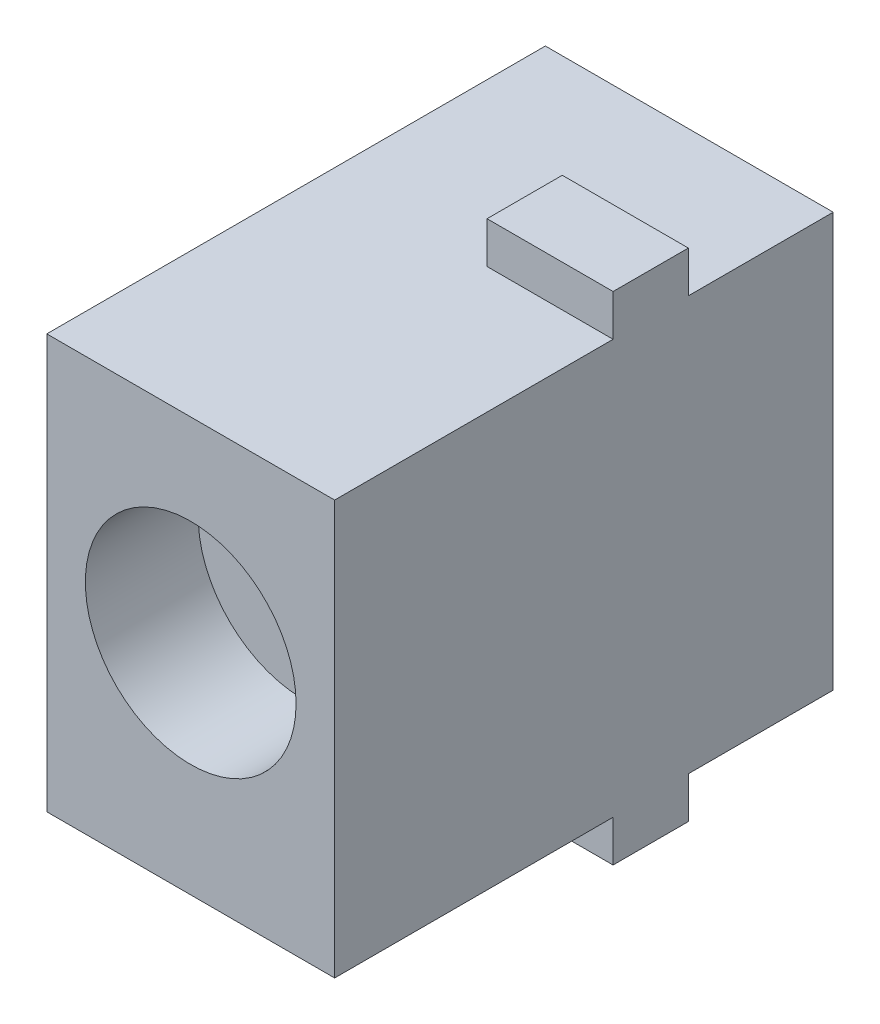
SolidWorks part; units mm, degrees
ref_plane "Спереди" through (0, 0, 0) normal (0, 0, 1) x (1, 0, 0)
ref_plane "Сверху" through (0, 0, 0) normal (0, 1, 0) x (1, 0, 0)
ref_plane "Справа" through (0, 0, 0) normal (1, 0, 0) x (0, 0, -1)
sketch "Эскиз1" plane through (0, 0, 0) normal (0, 0, 1) x (1, 0, 0)
  line L0 (0, 0) -> (-22117.764, 0) construction
  line L1 (0, 0) -> (0, 22117.764) construction
  line L3 (3.825, 5.5) -> (-3.825, 5.5)
  line L4 (3.825, 5.5) -> (3.825, -5.5)
  line L5 (3.825, -5.5) -> (-3.825, -5.5)
  line L6 (-3.825, 5.5) -> (-3.825, -5.5)
  line L7 (3.825, 5.5) -> (-3.825, -5.5) construction
  line L8 (3.825, -5.5) -> (-3.825, 5.5) construction
  point P5 (0, 0)
  dimension "D1" = 7.65
  dimension "D2" = 11
extrude "Бобышка-Вытянуть1" add sketch "Эскиз1" along normal blind 13.25
sketch "Эскиз2" plane through (0, 5.5, 0) normal (0, 1, 0) x (1, 0, 0)
  line L0 (3.825, -13.25) -> (3.825, 0) construction
  line L1 (3.825, -3.85) -> (0.475, -3.85)
  line L2 (3.825, -3.85) -> (3.825, -5.85)
  line L3 (3.825, -5.85) -> (0.475, -5.85)
  line L4 (0.475, -3.85) -> (0.475, -5.85)
  line L5 (3.825, -13.25) -> (-3.825, -13.25) construction
  dimension "D1" = 3.35
  dimension "D2" = 2
  dimension "D3" = 7.4
extrude "Бобышка-Вытянуть2" add sketch "Эскиз2" along normal blind 1.1
mirror "Зеркальное отражение1" about plane through (0, 0, 0) normal (0, 1, 0) of "Бобышка-Вытянуть2"
sketch "Эскиз3" plane through (0, 0, 13.25) normal (0, 0, 1) x (1, 0, 0)
  line L0 (0, 0) -> (0, -50000) construction
  line L3 (-3.825, -5.5) -> (3.825, -5.5) construction
  circle A0 centre (0, 0.3) radius 2.8
  point P5 (0, 2.1442)
  dimension "D1" = 5.6
  dimension "D2" = 3
extrude "Вырез-Вытянуть1" cut sketch "Эскиз3" against normal blind 3
